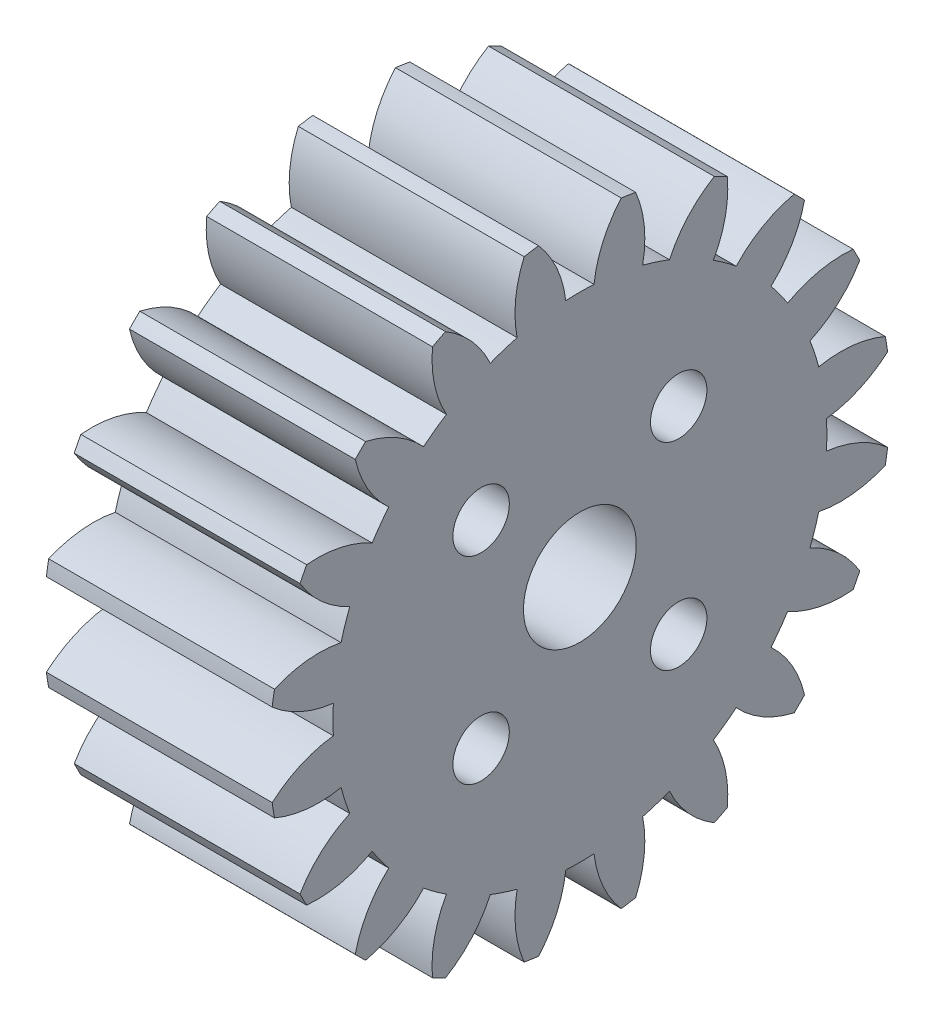
SolidWorks part; units mm, degrees
ref_plane "Plane1" through (0, 0, 0) normal (0, 0, 1) x (1, 0, 0)
ref_plane "Plane2" through (0, 0, 0) normal (0, 1, 0) x (1, 0, 0)
ref_plane "Plane3" through (0, 0, 0) normal (1, 0, 0) x (0, 0, -1)
sketch "HoldingSke" plane through (0, 0, 0) normal (0, 1, 0) x (1, 0, 0)
  line L0 (0, 0) -> (0.9397, -0.342)
  line L1 (-15, 0) -> (100, 0) construction
  line L2 (0, 0) -> (-2.1039, 2.3779)
  line L3 (0, 0) -> (-11.863, 4.5341)
  line L4 (0, 0) -> (8.1152, 2.9537)
  line L5 (0, 0) -> (-46.8476, -17.4728)
  line L6 (0, 0) -> (-6.6317, -4.4744)
  line L7 (-2.1039, 2.3779) -> (8.6586, 51.2059)
  line L8 (-76.2, 54.61) -> (-75.5, 54.61)
  line L9 (-71.009, 38.7566) -> (-53.1078, 45.2721)
  line L10 (-76.2, 71.12) -> (104.1128, 71.12)
  line L11 (0, 0) -> (-8, 0)
  line L12 (-76.2, 101.6) -> (-76.162, 101.6)
  line L13 (24.9733, 27.94) -> (52.9518, 28.4284)
  line L14 (24.9733, 27.94) -> (24.9743, 27.94)
  line L15 (24.9733, 27.94) -> (100.4006, 29.5858)
  line L16 (-63.627, -1) -> (-12.827, -1)
  circle A0 centre (0, 0) radius 2
  circle A1 centre (0, 0) radius 8.749
  circle A2 centre (0, 0) radius 37.5
  circle A3 centre (0, 0) radius 2
  dimension "MHD" = 17.498
  dimension "Hub_dia" = 75
  dimension "Bore" = 4
  dimension "MBD" = 4
  dimension "Num_teeth" = 20
  dimension "Pitch" = 1
  dimension "Overall_len" = 50
  dimension "Show_teeth" = 20
  dimension "Thickness" = 8
  dimension "OAL" = 50.0001
  dimension "T_dim" = 0.7
  dimension "Ap" = 20
  dimension "H" = 19.05
  dimension "Pitch_radius" = 180.3128
  dimension "Width" = 8
  dimension "Backlash" = 0.038
  dimension "Addendum_fac" = 1
  dimension "Dedendum_fac" = 1.25
  dimension "Clearance_fac" = 0.25
  dimension "Dedendum_add" = 0.001
  dimension "Module" = 1
sketch "BasProSke" plane through (0, 0, 0) normal (0, 1, 0) x (1, 0, 0)
  line L0 (-10, 0) -> (60, 0) construction
  line L1 (0, 0) -> (0, 11)
  line L2 (0, 0) -> (8, 0)
  line L3 (8, 0) -> (8, 11)
  line L4 (8, 11) -> (0, 11)
  dimension "Thickness" = 8
  dimension "Diameter" = 22
revolve "Base-Revolve" add sketch "BasProSke" angle 360 about L0
sketch "TooCutSke" plane through (0, 0, 0) normal (1, 0, 0) x (0, 0, -1)
  line L1 (0, 0) -> (0, 107) construction
  line L2 (0, 0) -> (-0.8511, 9.9637) construction
  line L3 (0, 0) -> (-3.1206, 19.7028) construction
  line L4 (-0.8511, 9.9637) -> (-1.5603, 9.8514) construction
  arc A0 (0.4999, 8.7347) -> (-0.4999, 8.7347) centre (0, 0) ccw
  arc A1 (1.4852, 10.9249) -> (-1.4852, 10.9249) centre (0, 0) ccw
  circle A2 centre (0, 0) radius 10 construction
  circle A3 centre (0, 0) radius 9.3969 construction
  arc A4 (-0.4999, 8.7347) -> (-1.4852, 10.9249) centre (-4.4722, 8.2645) ccw
  arc A5 (1.4852, 10.9249) -> (0.4999, 8.7347) centre (4.4722, 8.2645) ccw
  dimension "Root_dia" = 17.498
  dimension "Overcut_dia" = 22.0508
  dimension "Pitch_dia" = 20
  dimension "Base_dia" = 18.7939
  dimension "Flank_rad" = 4
  dimension "Half_ang" = 9
  dimension "Half_CT" = 0.7181
extrude "ToothCut" cut sketch "TooCutSke" along normal through all
fillet "Breaks" [suppressed] radius 0.02
fillet "RootFillets" [suppressed] radius 0.251
pattern_circular "TeethCuts" count 20 every 18 about axis through (-10, 0, 0) along (1, 0, 0) of "ToothCut", "RootFillets", "Breaks"
sketch "HubNeaOneSke" plane through (0, 0, 0) normal (-1, 0, 0) x (0, 0, 1)
  circle A0 centre (0, 0) radius 8.749
  dimension "Diameter" = 17.498
extrude "HubNearOne" [suppressed] add sketch "HubNeaOneSke" along normal blind 42.0001
sketch "HubNeaBotSke" plane through (0, 0, 0) normal (-1, 0, 0) x (0, 0, 1)
  circle A0 centre (0, 0) radius 8.749
  dimension "Diameter" = 17.498
extrude "HubNearBoth" [suppressed] add sketch "HubNeaBotSke" along normal blind 21
ref_plane "FarPln" through (8, 0, 0) normal (1, 0, 0) x (0, 0, -1)
sketch "HubFarSke" plane through (8, 0, 0) normal (1, 0, 0) x (0, 0, -1)
  circle A0 centre (0, 0) radius 8.749
  dimension "Diameter" = 17.498
extrude "HubFar" [suppressed] add sketch "HubFarSke" along normal blind 21
sketch "BorSke" plane through (0, 0, 0) normal (1, 0, 0) x (0, 0, -1)
  circle A0 centre (0, 0) radius 2
  dimension "Diameter" = 4
extrude "Bore" cut sketch "BorSke" along normal mid plane 100.0001
sketch "KeySke" plane through (0, 0, 0) normal (1, 0, 0) x (0, 0, -1)
  line L0 (-0.8, 0) -> (-0.8, 2.7)
  line L1 (-0.8, 2.7) -> (0.8, 2.7)
  line L2 (0.8, 2.7) -> (0.8, 0)
  line L3 (0, 0) -> (0, 34) construction
  line L4 (-0.8, 0) -> (0.8, 0)
  dimension "Offset" = 2.7
  dimension "Width" = 1.6
extrude "Keyway" [suppressed] cut sketch "KeySke" along normal mid plane 100.0001
pattern_circular "Keyway2" [suppressed] count 2 every 90 about axis through (-10, 0, 0) along (1, 0, 0)
sketch "Sketch1" plane through (8, 0, 0) normal (1, 0, 0) x (0, 0, -1)
  line L0 (0, 0) -> (-4.5, 0)
  line L1 (-4.5, 0) -> (-4.5, -4.5)
  line L2 (-4.5, -4.5) -> (-2.5, -4.5)
  line L3 (-2.5, -4.5) -> (-2.5, -2.25)
  line L4 (-2.5, -2.25) -> (-4.5, -2.25)
  line L5 (-4.5, -2.25) -> (-4.5, 4.5)
  line L6 (-4.5, 4.5) -> (-2.5, 4.5)
  line L7 (-2.5, 4.5) -> (-2.5, 2.5)
  line L8 (-2.5, 2.5) -> (-4.5, 2.5)
  line L9 (0, 0) -> (4.5, 0)
  line L10 (4.5, 0) -> (4.5, -4.5)
  line L11 (4.5, -4.5) -> (2.5, -4.5)
  line L12 (2.5, -4.5) -> (2.5, -2.5)
  line L13 (2.5, -2.5) -> (4.5, -2.5)
  line L14 (4.5, 0) -> (4.5, 4.5)
  line L15 (4.5, 4.5) -> (2.5, 4.5)
  line L16 (2.5, 4.5) -> (2.5, 2.5)
  line L17 (2.5, 2.5) -> (4.5, 2.5)
  line L18 (-4.5, -2.5) -> (-4.5, -4.5)
  line L19 (-4.5, -3.5) -> (4.5, -3.5)
  line L20 (4.5, 4.5) -> (4.5, 2.5)
  line L21 (4.5, 3.5) -> (-4.5, 3.5)
  circle A0 centre (-3.5, -3.5) radius 1
  circle A1 centre (3.5, -3.5) radius 1
  circle A2 centre (3.5, 3.5) radius 1
  circle A3 centre (-3.5, 3.5) radius 1
  dimension "D16" = 2
  dimension "D17" = 2
  dimension "D18" = 2
  dimension "D1" = 2
  dimension "D2" = 4.5
  dimension "D3" = 4.5
  dimension "D4" = 2
  dimension "D5" = 2
  dimension "D6" = 4.5
  dimension "D7" = 4.5
  dimension "D8" = 2
  dimension "D9" = 2
  dimension "D10" = 2
  dimension "D11" = 2
  dimension "D12" = 4.5
  dimension "D13" = 4.5
  dimension "D14" = 1
  dimension "D15" = 7
extrude "Cut-Extrude1" cut sketch "Sketch1" along normal blind 6 and the other way blind 13 contours L19 A0 | L19 A0 | L21 A3 | L21 A3 | L21 A2 | L21 A2 | L19 A1 | L19 A1
equation "' \"Module@HoldingSke\" = 6.35"
equation "' \"Num_teeth@HoldingSke\" = 12"
equation "' \"Ap@HoldingSke\" =  20"
equation "' \"Ap@HoldingSke\" = 20"
equation "' \"Width@HoldingSke\" = 0.5 * 25.4"
equation "' \"Hub_dia@HoldingSke\"= 1 * 25.4"
equation "' \"Hub_dia@HoldingSke\" = 1 * 25.4"
equation "' \"Overall_len@HoldingSke\" = 1.0 * 25.4"
equation "' \"Bore@HoldingSke\" = 0.75 * 25.4"
equation "' \"T_dim@HoldingSke\" = 0.1 * 25.4"
equation "' \"Width@KeySke\" = 0.25 * 25.4"
equation "' \"Show_teeth@HoldingSke\" = 13"
equation "' \"Backlash@HoldingSke\" = 0.009 * 25.4"
equation "' \"Addendum_fac@HoldingSke\" = 1.0"
equation "' \"Dedendum_fac@HoldingSke\" = 1.25"
equation "' \"Dedendum_add@HoldingSke\" = 0.00005 * 25.4"
equation "' \"Clearance_fac@HoldingSke\" = 0.25"
equation "\"Pitch@HoldingSke\" = 1 / \"Module@HoldingSke\""
equation "\"Overcut_dia@TooCutSke\" = (\"Num_teeth@HoldingSke\" + 2 * \"Addendum_fac@HoldingSke\") / \"Pitch@HoldingSke\" + 0.002 * 25.4"
equation "\"Pitch_dia@TooCutSke\" = \"Num_teeth@HoldingSke\" / \"Pitch@HoldingSke\""
equation "\"Base_dia@TooCutSke\" = \"Num_teeth@HoldingSke\" / \"Pitch@HoldingSke\" * cos((\"Ap@HoldingSke\"  * 3.14159265 / 180))"
equation "\"Root_dia@TooCutSke\" = (\"Num_teeth@HoldingSke\" + 2) / \"Pitch@HoldingSke\" - 2 * (\"Addendum_fac@HoldingSke\" + \"Dedendum_fac@HoldingSke\") / \"Pitch@HoldingSke\" - \"Dedendum_add@HoldingSke\" * 2"
equation "\"Half_ang@TooCutSke\" = 180 / \"Num_teeth@HoldingSke\""
equation "\"Half_CT@TooCutSke\" = \"Num_teeth@HoldingSke\" / \"Pitch@HoldingSke\" * sin((3.14159265 / 2 / \"Num_teeth@HoldingSke\")) / 2 - 7 * \"Backlash@HoldingSke\" / 4"
equation "\"Flank_rad@TooCutSke\" = \"Num_teeth@HoldingSke\" / \"Pitch@HoldingSke\" / 5"
equation "\"Radius@RootFillets\" = \"Clearance_fac@HoldingSke\" / \"Pitch@HoldingSke\" + \"Dedendum_add@HoldingSke\""
equation "\"Break_rad@Breaks\" = 0.02 / \"Pitch@HoldingSke\""
equation "\"Thickness@HoldingSke\" = \"Width@HoldingSke\""
equation "\"OAL@HoldingSke\" = \"Thickness@HoldingSke\""
equation "\"MHD@HoldingSke\" = (\"Num_teeth@HoldingSke\" + 2) / \"Pitch@HoldingSke\" - 2 * (\"Addendum_fac@HoldingSke\" + \"Dedendum_fac@HoldingSke\")  / \"Pitch@HoldingSke\" - \"Dedendum_add@HoldingSke\" * 2"
equation "\"MBD@HoldingSke\" = (\"Num_teeth@HoldingSke\" + 2) / \"Pitch@HoldingSke\" - 2 * (\"Addendum_fac@HoldingSke\" + \"Dedendum_fac@HoldingSke\")  / \"Pitch@HoldingSke\" - \"Dedendum_add@HoldingSke\" * 2 - 0.002 * 25.4"
equation "\"MHD@HoldingSke\" = ((sgn( \"MHD@HoldingSke\" - \"Hub_dia@HoldingSke\" )-1)*( \"MHD@HoldingSke\" - \"Hub_dia@HoldingSke\" ))/-2+ \"Hub_dia@HoldingSke\""
equation "\"MBD@HoldingSke\" = ((sgn( \"MBD@HoldingSke\" - \"Bore@HoldingSke\" )-1)*( \"MBD@HoldingSke\" - \"Bore@HoldingSke\" ))/-2+ \"Bore@HoldingSke\""
equation "\"OAL@HoldingSke\" = ((sgn( \"OAL@HoldingSke\" - \"Overall_len@HoldingSke\" )+1)*( \"OAL@HoldingSke\" - \"Overall_len@HoldingSke\" ))/2 + \"Overall_len@HoldingSke\" + 0.000002 * 25.4"
equation "\"Num_teeth@TeethCuts\" = int( \"Show_teeth@HoldingSke\" ) + 1"
equation "\"Num_teeth@TeethCuts\" = ((sgn( \"Num_teeth@TeethCuts\" - \"Num_teeth@HoldingSke\" )-1)*( \"Num_teeth@TeethCuts\" - \"Num_teeth@HoldingSke\" ))/-2+ \"Num_teeth@HoldingSke\""
equation "\"Num_teeth@TeethCuts\" = ((sgn( \"Num_teeth@TeethCuts\" - 2.0)+1)*( \"Num_teeth@TeethCuts\" - 2.0))/2 +2.0"
equation "\"Angle@TeethCuts\" = 360.0 / \"Num_teeth@HoldingSke\""
equation "\"Diameter@BasProSke\" = (\"Num_teeth@HoldingSke\" + 2 * \"Addendum_fac@HoldingSke\") / \"Pitch@HoldingSke\""
equation "\"Thickness@BasProSke\"  = \"Thickness@HoldingSke\""
equation "' \"Fillet_rad@BasProSke\" =  \"Thickness@HoldingSke\" * 0.05"
equation "' \"Fillet_rad@BasProSke\" = \"Thickness@HoldingSke\" * 0.05"
equation "\"MHD@HoldingSke\" = ((sgn( \"MHD@HoldingSke\" - \"Root_dia@TooCutSke\" )-1)*( \"MHD@HoldingSke\" - \"Root_dia@TooCutSke\" ))/-2+ \"Root_dia@TooCutSke\""
equation "\"Diameter@HubNeaOneSke\" = \"MHD@HoldingSke\""
equation "\"Length@HubNearOne\" = \"OAL@HoldingSke\" - \"Thickness@BasProSke\""
equation "\"Diameter@HubNeaBotSke\" = \"MHD@HoldingSke\""
equation "\"Length@HubNearBoth\" = ( \"OAL@HoldingSke\" - \"Thickness@BasProSke\" ) / 2.0"
equation "\"Thickness@FarPln\" = \"Thickness@BasProSke\""
equation "\"Diameter@HubFarSke\" = \"MHD@HoldingSke\""
equation "\"Length@HubFar\" = ( \"OAL@HoldingSke\" - \"Thickness@BasProSke\" ) / 2.0"
equation "\"Diameter@BorSke\" = \"MBD@HoldingSke\""
equation "\"D1@Bore\" = \"OAL@HoldingSke\" * 2.0"
equation "\"D1@Keyway\" = \"OAL@HoldingSke\" * 2.0"
equation "\"Offset@KeySke\" = \"T_dim@HoldingSke\" + \"MBD@HoldingSke\" / 2.0"
